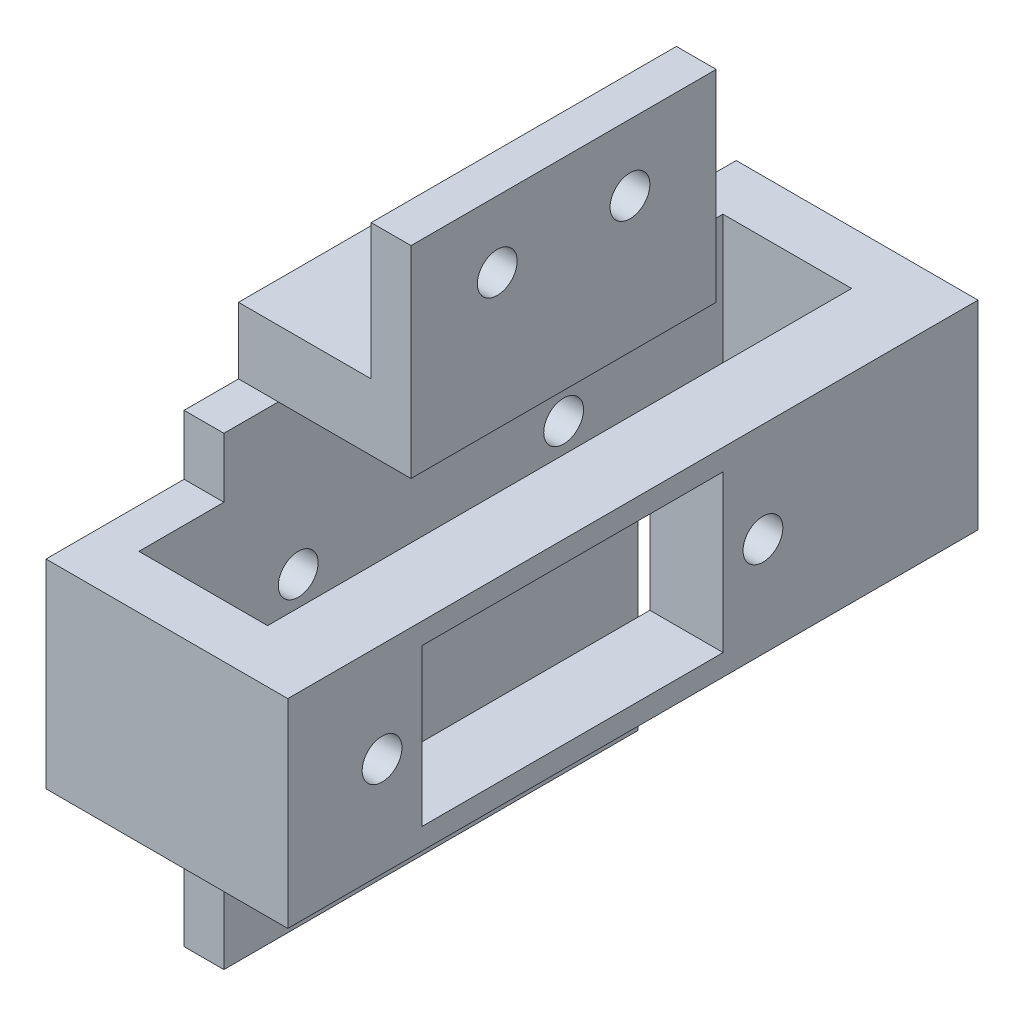
SolidWorks part; units mm, degrees
material "Plastique personnalisé"
ref_plane "Plan de face" through (0, 0, 0) normal (0, 0, 1) x (1, 0, 0)
ref_plane "Plan de dessus" through (0, 0, 0) normal (0, 1, 0) x (1, 0, 0)
ref_plane "Plan de droite" through (0, 0, 0) normal (1, 0, 0) x (0, 0, -1)
sketch "Esquisse1" plane through (0, 0, 0) normal (1, 0, 0) x (0, 0, -1)
  line L0 (0, -5) -> (23, -5) construction
  line L1 (0, 0) -> (23, 0)
  line L2 (0, 0) -> (0, -15.2)
  line L3 (0, -15.2) -> (23, -15.2)
  line L4 (23, 0) -> (23, -15.2)
  line L5 (11.5, 0) -> (11.5, -15.2) construction
  circle A0 centre (6.5, -5) radius 1.5
  circle A2 centre (16.5, -5) radius 1.5
  point P8 (11.5, -5)
  point P20 (11.5, -5)
  dimension "D5" = 3
  dimension "D1" = 15.2
  dimension "D2" = 23
  dimension "D3" = 5
  dimension "D4" = 5
extrude "Boss.-Extru.1" add sketch "Esquisse1" along normal blind 3
sketch "Esquisse2" plane through (0, 0, 0) normal (-1, 0, 0) x (0, 0, 1)
  line L0 (-23, -10.2) -> (0, -10.2)
  line L1 (-23, -15.2) -> (-23, 0) construction
  line L2 (0, 0) -> (0, -15.2) construction
  line L3 (0, -10.2) -> (0, -15.2)
  line L4 (0, -15.2) -> (-23, -15.2)
  line L6 (-23, -15.2) -> (-23, -10.2)
  dimension "D1" = 5
extrude "Boss.-Extru.2" add sketch "Esquisse2" along normal blind 10
sketch "Esquisse4" plane through (0, -15.2, 0) normal (0, -1, 0) x (1, 0, 0)
  line L7 (-10, -11.5) -> (3, -11.5) construction
  line L8 (-10, 4.1) -> (-7, 4.1)
  line L9 (-10, 4.1) -> (-10, -27.1)
  line L10 (-10, -27.1) -> (-7, -27.1)
  line L11 (-7, 4.1) -> (-7, -27.1)
  line L12 (-10, -23) -> (-10, 0) construction
  line L13 (3, 0) -> (3, -23) construction
  point P10 (-10, -11.5)
  dimension "D1" = 3
  dimension "D2" = 31.2
extrude "Boss.-Extru.3" add sketch "Esquisse4" along normal blind 35
fillet "Congé1" radius 10 2 edges at (-8.5, -50.2, 4.1) (-8.5, -50.2, -27.1)
sketch "Esquisse5" plane through (-7, 0, 0) normal (1, 0, 0) x (0, 0, -1)
  line L0 (11.5, -15.2) -> (11.5, -50.2) construction
  line L1 (23, -15.2) -> (0, -15.2) construction
  line L2 (17.1, -50.2) -> (5.9, -50.2) construction
  line L3 (0, -15.2) -> (23, -15.2) construction
  circle A0 centre (6.5, -45.2) radius 1.5
  circle A1 centre (1.5, -27.2) radius 1.5
  circle A2 centre (16.5, -45.2) radius 1.5
  circle A3 centre (21.5, -27.2) radius 1.5
  point P17 (21.5, -27.2)
  point P18 (1.5, -27.2)
  dimension "D1" = 3
  dimension "D2" = 3
  dimension "D3" = 10
  dimension "D4" = 5
  dimension "D5" = 12
  dimension "D6" = 5
sketch "Esquisse7" plane through (-7, 0, 0) normal (1, 0, 0) x (0, 0, -1)
  line L0 (-4.1, -40.2) -> (-4.1, -15.2) construction
  line L1 (-4.1, -19.7) -> (-14.5058, -19.7)
  line L2 (-4.1, -19.7) -> (-4.1, -34.7)
  line L3 (-4.1, -34.7) -> (-14.5058, -34.7)
  line L4 (-14.5058, -19.7) -> (-14.5058, -34.7)
  dimension "D1" = 7.5
  dimension "D2" = 15
  dimension "D3" = 10.4058
extrude "Boss.-Extru.4" add sketch "Esquisse7" against normal through all
sketch "Esquisse8" plane through (-7, 0, 0) normal (1, 0, 0) x (0, 0, -1)
  line L0 (-14.5058, -34.7) -> (-4.1, -34.7) construction
  line L3 (-14.5058, -19.7) -> (-10.5058, -19.7)
  line L4 (-14.5058, -19.7) -> (-14.5058, -34.7)
  line L5 (-14.5058, -34.7) -> (-10.5058, -34.7)
  line L6 (-10.5058, -19.7) -> (-10.5058, -34.7)
  dimension "D1" = 4
extrude "Boss.-Extru.5" add sketch "Esquisse8" along normal blind 9.7
sketch "Esquisse9" plane through (2.7, 0, 0) normal (1, 0, 0) x (0, 0, -1)
  line L0 (11.5, -15.2) -> (11.5, -50.2) construction
  line L1 (-14.5058, -19.7) -> (11.5, -19.7)
  line L2 (-14.5058, -19.7) -> (-14.5058, -34.7)
  line L3 (-14.5058, -34.7) -> (11.5, -34.7)
  line L4 (11.5, -19.7) -> (11.5, -34.7)
extrude "Boss.-Extru.6" add sketch "Esquisse9" along normal blind 5.52
ref_plane "Plan1" through (0, 0, -11.5) normal (0, 0, -1) x (-1, 0, 0)
mirror "Symétrie1" about plane through (8.22, -19.7, -11.5) normal (0, 0, 1) of "Boss.-Extru.2", "Boss.-Extru.5", "Boss.-Extru.6", "Boss.-Extru.4", "Boss.-Extru.3"
sketch "Esquisse10" plane through (8.22, 0, 0) normal (1, 0, 0) x (0, 0, -1)
  line L0 (-14.5058, -27.2) -> (37.5058, -27.2) construction
  line L1 (-4.4, -21.3) -> (18.3, -21.3)
  line L2 (-4.4, -21.3) -> (-4.4, -33.1)
  line L3 (-4.4, -33.1) -> (18.3, -33.1)
  line L4 (18.3, -21.3) -> (18.3, -33.1)
  line L5 (-14.5058, -19.7) -> (-14.5058, -34.7) construction
  line L6 (37.5058, -19.7) -> (37.5058, -34.7) construction
  line L8 (6.95, -21.3) -> (6.95, -34.7) construction
  line L9 (-14.5058, -34.7) -> (37.5058, -34.7) construction
  circle A0 centre (1.5, -27.2) radius 1.5
  circle A1 centre (-7.4, -27.2) radius 1.5
  circle A2 centre (21.3, -27.2) radius 1.5
  point P7 (-4.4, -27.2)
  dimension "D1" = 3
  dimension "D5" = 3
  dimension "D2" = 22.7
  dimension "D3" = 5.9
  dimension "D4" = 11.8
  dimension "D6" = 3
extrude "Enlèv. mat.-Extru.2" cut sketch "Esquisse10" against normal blind 5.52 contours A0 L0 | L0 A0 | L2 L0 A0 L4 L1 | L0 L2 L3 L4 A0 | A1 | A2
extrude "Enlèv. mat.-Extru.3" cut sketch "Esquisse5" against normal blind 10
